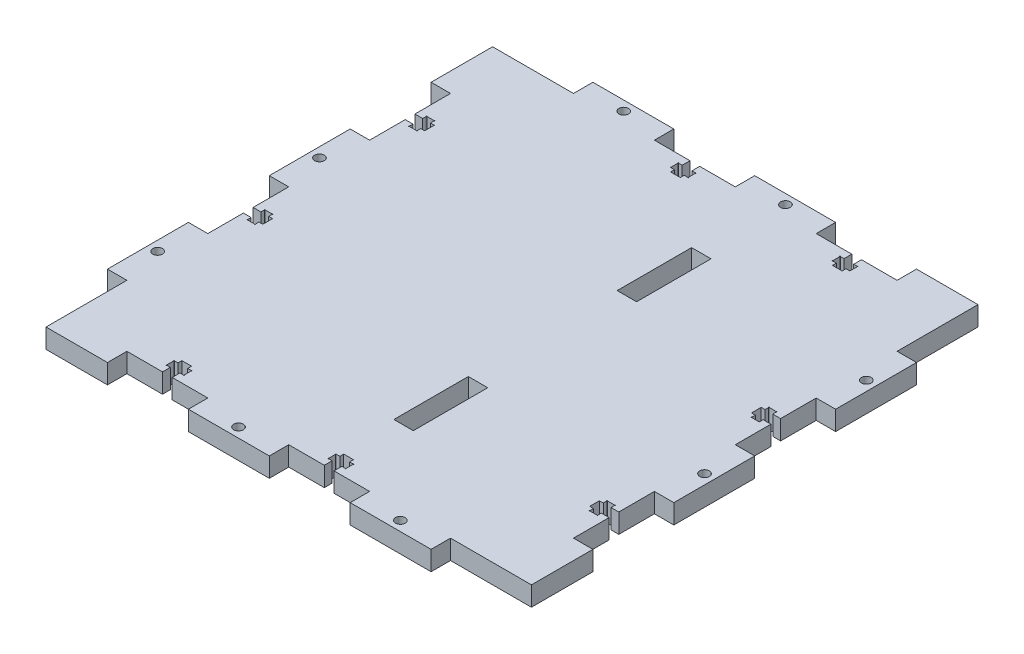
SolidWorks part; units mm, degrees
ref_plane "Front Plane" through (0, 0, 0) normal (0, 0, 1) x (1, 0, 0)
ref_plane "Top Plane" through (0, 0, 0) normal (0, 1, 0) x (1, 0, 0)
ref_plane "Right Plane" through (0, 0, 0) normal (1, 0, 0) x (0, 0, -1)
sketch "Sketch1" plane through (0, 0, 0) normal (0, 1, 0) x (1, 0, 0)
  line L0 (0, 75) -> (25, 75)
  line L1 (-50, 75) -> (-25, 75)
  line L2 (-75, 69) -> (-75, 50)
  line L3 (-69, -75) -> (-50, -75)
  line L4 (75, 50) -> (75, 25)
  line L7 (-75, 69) -> (-50, 69)
  line L8 (-50, 75) -> (-50, 69)
  line L10 (-25, 75) -> (-25, 69)
  line L11 (-25, 69) -> (0, 69)
  line L12 (0, 75) -> (0, 69)
  line L13 (50, 75) -> (69, 75)
  line L15 (25, 75) -> (25, 69)
  line L16 (25, 69) -> (50, 69)
  line L17 (50, 75) -> (50, 69)
  line L18 (75, 0) -> (75, -25)
  line L21 (75, 50) -> (69, 50)
  line L22 (69, 75) -> (69, 50)
  line L23 (75, 25) -> (69, 25)
  line L25 (75, 0) -> (69, 0)
  line L26 (69, 25) -> (69, 0)
  line L27 (75, -25) -> (69, -25)
  line L29 (75, -50) -> (69, -50)
  line L30 (69, -25) -> (69, -50)
  line L31 (75, -50) -> (75, -69)
  line L32 (25, -75) -> (50, -75)
  line L35 (75, -69) -> (50, -69)
  line L36 (50, -75) -> (50, -69)
  line L38 (25, -75) -> (25, -69)
  line L39 (25, -69) -> (0, -69)
  line L40 (0, -75) -> (0, -69)
  line L42 (-25, -75) -> (-25, -69)
  line L43 (-25, -69) -> (-50, -69)
  line L44 (-50, -75) -> (-50, -69)
  line L45 (-25, -75) -> (0, -75)
  line L46 (-75, 25) -> (-75, 0)
  line L49 (-75, -50) -> (-69, -50)
  line L50 (-69, -75) -> (-69, -50)
  line L51 (-75, -25) -> (-69, -25)
  line L53 (-75, 0) -> (-69, 0)
  line L54 (-69, -25) -> (-69, 0)
  line L55 (-75, 25) -> (-69, 25)
  line L57 (-75, 50) -> (-69, 50)
  line L58 (-69, 25) -> (-69, 50)
  line L59 (-75, -25) -> (-75, -50)
  dimension "D1" = 150
  dimension "D2" = 150
  dimension "D3" = 25
  dimension "D4" = 6
  dimension "D5" = 25
  dimension "25" = 25
  dimension "D6" = 25
  dimension "D7" = 6
  dimension "D8" = 6
  dimension "D9" = 25
  dimension "D10" = 25
  dimension "D11" = 6
  dimension "D12" = 25
  dimension "D13" = 6
  dimension "D14" = 25
  dimension "D15" = 25
  dimension "D16" = 6
  dimension "D17" = 25
  dimension "D18" = 19
  dimension "D19" = 6
  dimension "D20" = 25
  dimension "D21" = 25
  dimension "D22" = 25
  dimension "D23" = 6
  dimension "D24" = 6
  dimension "D25" = 25
  dimension "D26" = 25
  dimension "D27" = 19
  dimension "D28" = 6
  dimension "D29" = 25
  dimension "D30" = 25
  dimension "D31" = 6
  dimension "D32" = 25
  dimension "D33" = 25
  dimension "D34" = 6
  dimension "D35" = 25
  dimension "D36" = 19
extrude "Boss-Extrude1" add sketch "Sketch1" along normal blind 6
sketch "Sketch2" plane through (0, 6, 0) normal (0, 1, 0) x (1, 0, 0)
  line L0 (-25, 75) -> (-50, 75) construction
  line L1 (-25, 69) -> (-25, 75) construction
  line L2 (25, 75) -> (0, 75) construction
  line L3 (25, 69) -> (25, 75) construction
  line L4 (75, 25) -> (75, 50) construction
  line L5 (75, 50) -> (69, 50) construction
  line L6 (75, -25) -> (75, 0) construction
  line L7 (75, 0) -> (69, 0) construction
  line L8 (25, -75) -> (50, -75) construction
  line L9 (50, -75) -> (50, -69) construction
  line L10 (-25, -75) -> (0, -75) construction
  line L11 (0, -75) -> (0, -69) construction
  line L12 (-69, -25) -> (-75, -25) construction
  line L13 (-75, -25) -> (-75, -50) construction
  line L14 (-75, 25) -> (-75, 0) construction
  line L15 (-75, 0) -> (-69, 0) construction
  line L16 (-11, 69) -> (-14, 69)
  line L59 (0, 69) -> (-25, 69) construction
  line L60 (-14, 69) -> (-14, 66.6)
  line L61 (-14, 66.6) -> (-15.1, 66.6)
  line L63 (-15.2, 66.5) -> (-15.2, 64.3)
  line L65 (-15.1, 64.2) -> (-14, 64.2)
  line L66 (-14, 64.2) -> (-14, 63)
  line L67 (-14, 63) -> (-11, 63)
  line L69 (-12.5, 69) -> (-12.5, 63) construction
  line L72 (-11, 64.2) -> (-11, 63)
  line L73 (-9.9, 64.2) -> (-11, 64.2)
  line L74 (-9.8, 66.5) -> (-9.8, 64.3)
  line L75 (-11, 66.6) -> (-9.9, 66.6)
  line L76 (-11, 69) -> (-11, 66.6)
  line L91 (69, 11) -> (69, 14)
  line L92 (69, 14) -> (66.6, 14)
  line L93 (66.6, 14) -> (66.6, 15.1)
  line L94 (66.5, 15.2) -> (64.3, 15.2)
  line L95 (64.2, 15.1) -> (64.2, 14)
  line L96 (64.2, 14) -> (63, 14)
  line L97 (63, 14) -> (63, 11)
  line L98 (69, 12.5) -> (63, 12.5) construction
  line L99 (64.2, 11) -> (63, 11)
  line L100 (64.2, 9.9) -> (64.2, 11)
  line L101 (66.5, 9.8) -> (64.3, 9.8)
  line L102 (66.6, 11) -> (66.6, 9.9)
  line L103 (69, 11) -> (66.6, 11)
  line L104 (69, 0) -> (69, 25) construction
  line L105 (39, 69) -> (36, 69)
  line L106 (36, 69) -> (36, 66.6)
  line L107 (36, 66.6) -> (34.9, 66.6)
  line L108 (34.8, 66.5) -> (34.8, 64.3)
  line L109 (34.9, 64.2) -> (36, 64.2)
  line L110 (36, 64.2) -> (36, 63)
  line L111 (36, 63) -> (39, 63)
  line L112 (37.5, 69) -> (37.5, 63) construction
  line L113 (39, 64.2) -> (39, 63)
  line L114 (40.1, 64.2) -> (39, 64.2)
  line L115 (40.2, 66.5) -> (40.2, 64.3)
  line L116 (39, 66.6) -> (40.1, 66.6)
  line L117 (39, 69) -> (39, 66.6)
  line L118 (50, 69) -> (25, 69) construction
  line L119 (69, -39) -> (69, -36)
  line L120 (69, -36) -> (66.6, -36)
  line L121 (66.6, -36) -> (66.6, -34.9)
  line L122 (66.5, -34.8) -> (64.3, -34.8)
  line L123 (64.2, -34.9) -> (64.2, -36)
  line L124 (64.2, -36) -> (63, -36)
  line L125 (63, -36) -> (63, -39)
  line L126 (69, -37.5) -> (63, -37.5) construction
  line L127 (64.2, -39) -> (63, -39)
  line L128 (64.2, -40.1) -> (64.2, -39)
  line L129 (66.5, -40.2) -> (64.3, -40.2)
  line L130 (66.6, -39) -> (66.6, -40.1)
  line L131 (69, -39) -> (66.6, -39)
  line L132 (69, -50) -> (69, -25) construction
  line L133 (11, -69) -> (14, -69)
  line L134 (14, -69) -> (14, -66.6)
  line L135 (14, -66.6) -> (15.1, -66.6)
  line L136 (15.2, -66.5) -> (15.2, -64.3)
  line L137 (15.1, -64.2) -> (14, -64.2)
  line L138 (14, -64.2) -> (14, -63)
  line L139 (14, -63) -> (11, -63)
  line L140 (12.5, -69) -> (12.5, -63) construction
  line L141 (11, -64.2) -> (11, -63)
  line L142 (9.9, -64.2) -> (11, -64.2)
  line L143 (9.8, -66.5) -> (9.8, -64.3)
  line L144 (11, -66.6) -> (9.9, -66.6)
  line L145 (11, -69) -> (11, -66.6)
  line L146 (0, -69) -> (25, -69) construction
  line L147 (-39, -69) -> (-36, -69)
  line L148 (-36, -69) -> (-36, -66.6)
  line L149 (-36, -66.6) -> (-34.9, -66.6)
  line L150 (-34.8, -66.5) -> (-34.8, -64.3)
  line L151 (-34.9, -64.2) -> (-36, -64.2)
  line L152 (-36, -64.2) -> (-36, -63)
  line L153 (-36, -63) -> (-39, -63)
  line L154 (-37.5, -69) -> (-37.5, -63) construction
  line L155 (-39, -64.2) -> (-39, -63)
  line L156 (-40.1, -64.2) -> (-39, -64.2)
  line L157 (-40.2, -66.5) -> (-40.2, -64.3)
  line L158 (-39, -66.6) -> (-40.1, -66.6)
  line L159 (-39, -69) -> (-39, -66.6)
  line L160 (-50, -69) -> (-25, -69) construction
  line L161 (-69, 39) -> (-69, 36)
  line L162 (-69, 36) -> (-66.6, 36)
  line L163 (-66.6, 36) -> (-66.6, 34.9)
  line L164 (-66.5, 34.8) -> (-64.3, 34.8)
  line L165 (-64.2, 34.9) -> (-64.2, 36)
  line L166 (-64.2, 36) -> (-63, 36)
  line L167 (-63, 36) -> (-63, 39)
  line L168 (-69, 37.5) -> (-63, 37.5) construction
  line L169 (-64.2, 39) -> (-63, 39)
  line L170 (-64.2, 40.1) -> (-64.2, 39)
  line L171 (-66.5, 40.2) -> (-64.3, 40.2)
  line L172 (-66.6, 39) -> (-66.6, 40.1)
  line L173 (-69, 39) -> (-66.6, 39)
  line L174 (-69, 50) -> (-69, 25) construction
  line L175 (-69, -11) -> (-69, -14)
  line L176 (-69, -14) -> (-66.6, -14)
  line L177 (-66.6, -14) -> (-66.6, -15.1)
  line L178 (-66.5, -15.2) -> (-64.3, -15.2)
  line L179 (-64.2, -15.1) -> (-64.2, -14)
  line L180 (-64.2, -14) -> (-63, -14)
  line L181 (-63, -14) -> (-63, -11)
  line L182 (-69, -12.5) -> (-63, -12.5) construction
  line L183 (-64.2, -11) -> (-63, -11)
  line L184 (-64.2, -9.9) -> (-64.2, -11)
  line L185 (-66.5, -9.8) -> (-64.3, -9.8)
  line L186 (-66.6, -11) -> (-66.6, -9.9)
  line L187 (-69, -11) -> (-66.6, -11)
  line L188 (-69, 0) -> (-69, -25) construction
  circle A0 centre (-37.5, 72) radius 1.5
  circle A1 centre (12.5, 72) radius 1.5
  circle A2 centre (72, 37.5) radius 1.5
  circle A3 centre (72, -12.5) radius 1.5
  circle A4 centre (37.5, -72) radius 1.5
  circle A5 centre (-12.5, -72) radius 1.5
  circle A6 centre (-72, -37.5) radius 1.5
  circle A7 centre (-72, 12.5) radius 1.5
  arc A9 (-15.1, 66.6) -> (-15.2, 66.5) centre (-15.2, 66.6) ccw
  arc A10 (-15.2, 64.3) -> (-15.1, 64.2) centre (-15.2, 64.2) ccw
  arc A11 (-9.8, 64.3) -> (-9.9, 64.2) centre (-9.8, 64.2) cw
  arc A12 (-9.9, 66.6) -> (-9.8, 66.5) centre (-9.8, 66.6) cw
  arc A17 (66.6, 15.1) -> (66.5, 15.2) centre (66.6, 15.2) ccw
  arc A18 (64.3, 15.2) -> (64.2, 15.1) centre (64.2, 15.2) ccw
  arc A19 (64.3, 9.8) -> (64.2, 9.9) centre (64.2, 9.8) cw
  arc A20 (66.6, 9.9) -> (66.5, 9.8) centre (66.6, 9.8) cw
  arc A21 (34.9, 66.6) -> (34.8, 66.5) centre (34.8, 66.6) ccw
  arc A22 (34.8, 64.3) -> (34.9, 64.2) centre (34.8, 64.2) ccw
  arc A23 (40.2, 64.3) -> (40.1, 64.2) centre (40.2, 64.2) cw
  arc A24 (40.1, 66.6) -> (40.2, 66.5) centre (40.2, 66.6) cw
  arc A25 (66.6, -34.9) -> (66.5, -34.8) centre (66.6, -34.8) ccw
  arc A26 (64.3, -34.8) -> (64.2, -34.9) centre (64.2, -34.8) ccw
  arc A27 (64.3, -40.2) -> (64.2, -40.1) centre (64.2, -40.2) cw
  arc A28 (66.6, -40.1) -> (66.5, -40.2) centre (66.6, -40.2) cw
  arc A29 (15.1, -66.6) -> (15.2, -66.5) centre (15.2, -66.6) ccw
  arc A30 (15.2, -64.3) -> (15.1, -64.2) centre (15.2, -64.2) ccw
  arc A31 (9.8, -64.3) -> (9.9, -64.2) centre (9.8, -64.2) cw
  arc A32 (9.9, -66.6) -> (9.8, -66.5) centre (9.8, -66.6) cw
  arc A33 (-34.9, -66.6) -> (-34.8, -66.5) centre (-34.8, -66.6) ccw
  arc A34 (-34.8, -64.3) -> (-34.9, -64.2) centre (-34.8, -64.2) ccw
  arc A35 (-40.2, -64.3) -> (-40.1, -64.2) centre (-40.2, -64.2) cw
  arc A36 (-40.1, -66.6) -> (-40.2, -66.5) centre (-40.2, -66.6) cw
  arc A37 (-66.6, 34.9) -> (-66.5, 34.8) centre (-66.6, 34.8) ccw
  arc A38 (-64.3, 34.8) -> (-64.2, 34.9) centre (-64.2, 34.8) ccw
  arc A39 (-64.3, 40.2) -> (-64.2, 40.1) centre (-64.2, 40.2) cw
  arc A40 (-66.6, 40.1) -> (-66.5, 40.2) centre (-66.6, 40.2) cw
  arc A41 (-66.6, -15.1) -> (-66.5, -15.2) centre (-66.6, -15.2) ccw
  arc A42 (-64.3, -15.2) -> (-64.2, -15.1) centre (-64.2, -15.2) ccw
  arc A43 (-64.3, -9.8) -> (-64.2, -9.9) centre (-64.2, -9.8) cw
  arc A44 (-66.6, -9.9) -> (-66.5, -9.8) centre (-66.6, -9.8) cw
  point P83 (-12.5, 69)
  point P104 (69, 12.5)
  point P122 (37.5, 69)
  point P148 (69, -37.5)
  point P174 (12.5, -69)
  point P196 (-37.5, -69)
  point P222 (-69, 37.5)
  point P246 (-69, -12.5)
  dimension "D1" = 3
  dimension "D3" = 3
  dimension "D5" = 3
  dimension "D7" = 3
  dimension "D9" = 3
  dimension "D11" = 3
  dimension "D13" = 12.5
  dimension "D15" = 3
  dimension "D32" = 3
  dimension "D31" = 3
  dimension "D17" = 3
  dimension "D29" = 3
  dimension "D30" = 3
  dimension "D33" = 3
  dimension "D34" = 3
  dimension "D35" = 3
  dimension "D36" = 3
  dimension "D2" = 12.5
  dimension "D4" = 12.5
  dimension "D6" = 12.5
  dimension "D8" = 12.5
  dimension "D10" = 12.5
  dimension "D12" = 12.5
  dimension "D14" = 3
  dimension "D16" = 12.5
  dimension "D18" = 6
  dimension "D19" = 5.4
  dimension "D20" = 2.4
  dimension "D21" = 1.2
  dimension "D22" = 0.1
  dimension "D23" = 3
  dimension "D24" = 6
  dimension "D25" = 5.4
  dimension "D26" = 2.4
  dimension "D27" = 1.2
  dimension "D28" = 0.1
  dimension "D37" = 3
  dimension "D38" = 6
  dimension "D39" = 5.4
  dimension "D40" = 2.4
  dimension "D41" = 1.2
  dimension "D42" = 0.1
  dimension "D43" = 3
  dimension "D44" = 6
  dimension "D45" = 5.4
  dimension "D46" = 2.4
  dimension "D47" = 1.2
  dimension "D48" = 0.1
  dimension "D49" = 3
  dimension "D50" = 6
  dimension "D51" = 5.4
  dimension "D52" = 2.4
  dimension "D53" = 1.2
  dimension "D54" = 0.1
  dimension "D55" = 3
  dimension "D56" = 6
  dimension "D57" = 5.4
  dimension "D58" = 2.4
  dimension "D59" = 1.2
  dimension "D60" = 0.1
  dimension "D61" = 3
  dimension "D62" = 6
  dimension "D63" = 5.4
  dimension "D64" = 2.4
  dimension "D65" = 1.2
  dimension "D66" = 0.1
  dimension "D67" = 3
  dimension "D68" = 6
  dimension "D69" = 5.4
  dimension "D70" = 2.4
  dimension "D71" = 1.2
  dimension "D72" = 0.1
extrude "Cut-Extrude1" cut sketch "Sketch2" against normal through all
sketch "Sketch3" plane through (0, 0, 0) normal (0, -1, 0) x (1, 0, 0)
  line L0 (12.5, 63) -> (12.5, -75) construction
  line L1 (14, 63) -> (11, 63) construction
  line L2 (25, -75) -> (0, -75) construction
  line L3 (69, 0) -> (-69, 0) construction
  line L4 (15.5, 46) -> (9.5, 46)
  line L9 (9.5, 46) -> (9.5, 23)
  line L10 (9.5, 23) -> (15.5, 23)
  line L15 (15.5, 23) -> (15.5, 46)
  line L16 (9.5, -46) -> (9.5, -23)
  line L17 (15.5, -46) -> (9.5, -46)
  line L18 (15.5, -23) -> (15.5, -46)
  line L19 (9.5, -23) -> (15.5, -23)
  point P13 (12.5, 46)
  dimension "D1" = 23
  dimension "D2" = 6
  dimension "D3" = 23
extrude "Cut-Extrude2" cut sketch "Sketch3" against normal through all
